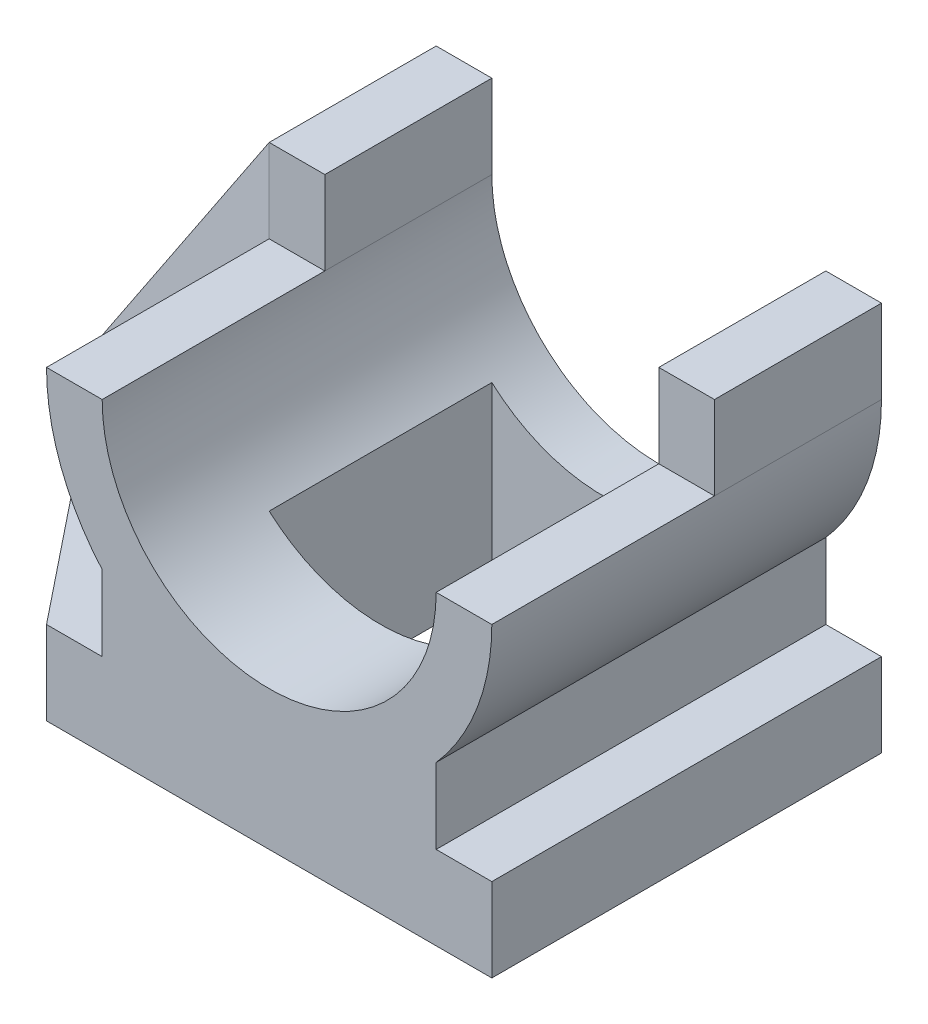
SolidWorks part; units mm, degrees
ref_plane "Front Plane" through (0, 0, 0) normal (0, 0, 1) x (1, 0, 0)
ref_plane "Top Plane" through (0, 0, 0) normal (0, 1, 0) x (1, 0, 0)
ref_plane "Right Plane" through (0, 0, 0) normal (1, 0, 0) x (0, 0, -1)
sketch "Sketch1" plane through (0, 0, 0) normal (0, 1, 0) x (1, 0, 0)
  line L0 (0, 0) -> (40, 0)
  line L1 (40, 0) -> (40, -70)
  line L2 (40, -70) -> (0, -70)
  line L3 (0, -70) -> (0, 0)
  dimension "D1" = 40
  dimension "D2" = 70
extrude "Boss-Extrude1" add sketch "Sketch1" along normal blind 15
sketch "Sketch2" plane through (0, 0, 0) normal (0, 0, 1) x (1, 0, 0)
  line L0 (0, 15) -> (30, 15)
  line L1 (30, 15) -> (30, 28.5425)
  line L2 (40, 55) -> (0, 55)
  line L3 (0, 55) -> (0, 15)
  arc A0 (30, 28.5425) -> (40, 55) centre (0, 55) ccw
  dimension "D3" = 40
  dimension "D1" = 30
  dimension "D2" = 40
extrude "Boss-Extrude2" add sketch "Sketch2" along normal blind 70
sketch "Sketch3" plane through (0, 0, 0) normal (0, 0, 1) x (1, 0, 0)
  line L0 (30, 55) -> (40, 55)
  line L1 (40, 55) -> (40, 70)
  line L2 (40, 70) -> (30, 70)
  line L3 (30, 70) -> (30, 55)
  dimension "D1" = 10
  dimension "D2" = 15
extrude "Boss-Extrude3" add sketch "Sketch3" along normal blind 30
mirror "Mirror1" about plane through (0, 0, 0) normal (1, 0, 0) of "Boss-Extrude3", "Boss-Extrude2", "Boss-Extrude1"
sketch "Sketch4" plane through (0, 0, 0) normal (0, 0, 1) x (1, 0, 0)
  line L0 (0, 20) -> (0, 75) construction
  line L1 (-30, 72) -> (-30, 55)
  line L2 (30, 55) -> (30, 72)
  line L3 (30, 72) -> (-30, 72)
  arc A0 (-30, 55) -> (30, 55) centre (0, 55) ccw
  dimension "D1" = 30
  dimension "D2" = 60
extrude "Cut-Extrude1" cut sketch "Sketch4" against normal through all and the other way through all
sketch "Sketch5" plane through (0, 0, 0) normal (0, 1, 0) x (1, 0, 0)
  line L0 (0, 0) -> (0, -70) construction
  line L1 (-20, -10) -> (20, -10)
  line L2 (20, -10) -> (20, -50)
  line L3 (20, -50) -> (-20, -50)
  line L4 (-20, -50) -> (-20, -10)
  dimension "D1" = 40
  dimension "D2" = 40
extrude "Cut-Extrude2" cut sketch "Sketch5" against normal through all and the other way through all
sketch "Sketch6" plane through (0, 0, 0) normal (0, 1, 0) x (1, 0, 0)
  line L0 (-40, 0) -> (-80, 0)
  line L1 (-80, 0) -> (-80, -20)
  line L2 (-80, -20) -> (-40, -70)
  line L3 (-40, -70) -> (-40, 0)
  dimension "D1" = 40
  dimension "D2" = 20
  dimension "D3" = 70
extrude "Boss-Extrude4" add sketch "Sketch6" along normal blind 15
sketch "Sketch7" plane through (0, 0, 0) normal (0, 0, 1) x (1, 0, 0)
  line L0 (-80, 15) -> (-40, 70)
  line L1 (-40, 70) -> (-40, 55)
  line L2 (-40, 55) -> (-30, 55)
  line L3 (-30, 55) -> (-30, 15)
  line L4 (-30, 15) -> (-80, 15)
  dimension "D1" = 15
  dimension "D2" = 10
  dimension "D3" = 50
extrude "Boss-Extrude5" add sketch "Sketch7" along normal blind 30
sketch "Sketch8" plane through (0, 0, 0) normal (0, 1, 0) x (1, 0, 0)
  line L0 (-80, -20) -> (-40, -30)
  line L1 (-40, -30) -> (-80, -30)
  line L2 (-80, -30) -> (-80, -20)
  dimension "D1" = 40
  dimension "D2" = 10
extrude "Cut-Extrude3" cut sketch "Sketch8" along normal blind 60 from offset 15
